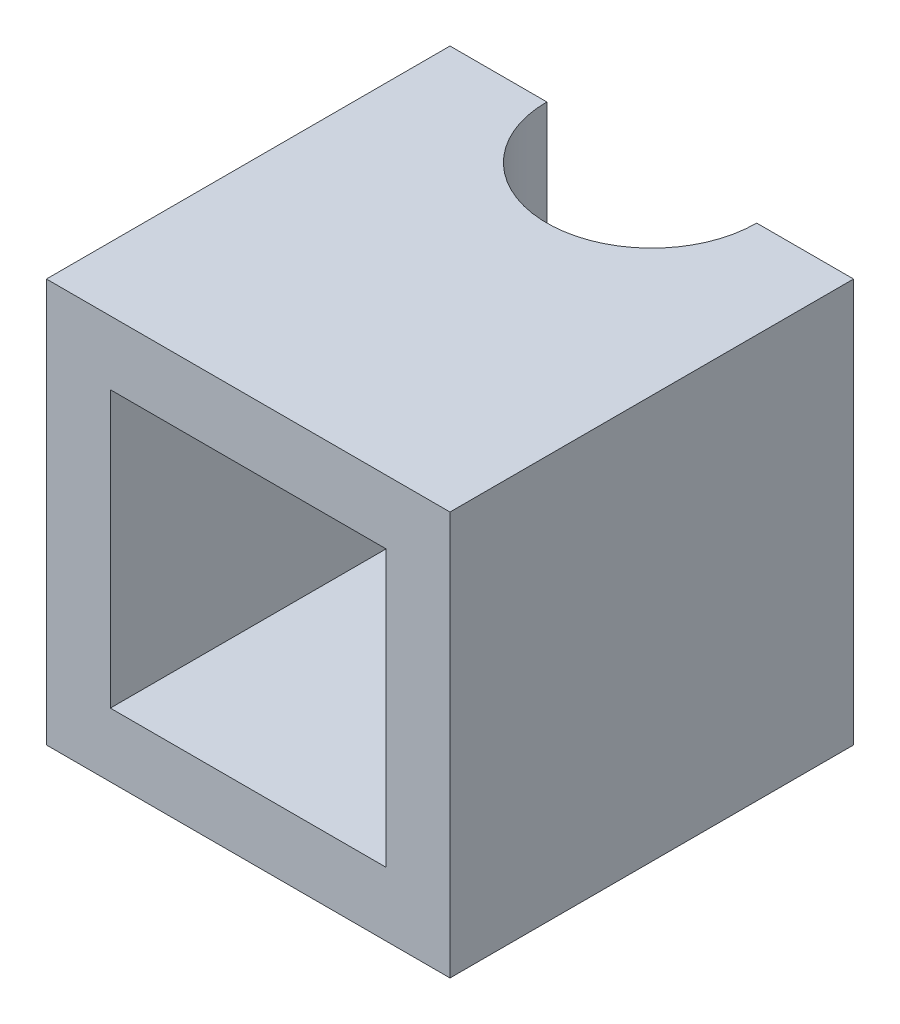
SolidWorks part; units mm, degrees
material "ABS"
ref_plane "Front Plane" through (0, 0, 0) normal (0, 0, 1) x (1, 0, 0)
ref_plane "Top Plane" through (0, 0, 0) normal (0, 1, 0) x (1, 0, 0)
ref_plane "Right Plane" through (0, 0, 0) normal (1, 0, 0) x (0, 0, -1)
sketch "Sketch1" plane through (0, 0, 0) normal (0, 0, 1) x (1, 0, 0)
  line L1 (-15, -15) -> (15, -15)
  line L2 (-15, -15) -> (-15, 15)
  line L3 (-15, 15) -> (15, 15)
  line L4 (15, -15) -> (15, 15)
  line L5 (-15, -15) -> (15, 15) construction
  line L6 (-15, 15) -> (15, -15) construction
  line L7 (-10.25, -10.25) -> (10.25, -10.25)
  line L8 (-10.25, -10.25) -> (-10.25, 10.25)
  line L9 (-10.25, 10.25) -> (10.25, 10.25)
  line L10 (10.25, -10.25) -> (10.25, 10.25)
  line L11 (-10.25, -10.25) -> (10.25, 10.25) construction
  line L12 (-10.25, 10.25) -> (10.25, -10.25) construction
  point P0 (0, 0)
  point P6 (0, 0)
  dimension "D1" = 30
  dimension "D2" = 20.5
  dimension "D3" = 20.5
extrude "Boss-Extrude1" add sketch "Sketch1" along normal blind 20
sketch "Sketch2" plane through (0, 0, 0) normal (0, 0, -1) x (-1, 0, 0)
  line L1 (-15, -15) -> (15, -15)
  line L2 (-15, -15) -> (-15, 15)
  line L3 (-15, 15) -> (15, 15)
  line L4 (15, -15) -> (15, 15)
  line L5 (-15, -15) -> (15, 15) construction
  line L6 (-15, 15) -> (15, -15) construction
  point P0 (0, 0)
extrude "Boss-Extrude3" add sketch "Sketch2" along normal blind 10
sketch "Sketch4" plane through (0, 0, -10) normal (0, 0, -1) x (-1, 0, 0)
  line L0 (0, 0) -> (0, 15)
  line L1 (15, 15) -> (-15, 15) construction
  line L2 (0, 15) -> (7.8, 15)
  line L3 (7.8, 15) -> (7.8, 8.75)
  line L10 (7.8, 7.65) -> (7.8, 8.75)
  line L19 (0, 0) -> (7.8, 0)
  line L20 (10.8, 9.95) -> (12.3, 9.95)
  line L21 (10.8, 9.95) -> (10.8, 6.45)
  line L22 (10.8, 6.45) -> (12.3, 6.45)
  line L23 (12.3, 9.95) -> (12.3, 6.45)
  line L24 (7.8, 0) -> (7.8, 7.65)
  dimension "D1" = 7.8
  dimension "D2" = 6.25
  dimension "D5" = 3
  dimension "D7" = 3.5
  dimension "D10" = 1.5
revolve "Cut-Revolve1" cut sketch "Sketch4" angle 180 about L0
sketch "Sketch5" plane through (0, 0, 0) normal (0, 0, 1) x (1, 0, 0)
  line L1 (-7.1617, 6.45) -> (7.1617, 6.45)
  line L2 (-7.1617, 6.45) -> (-7.1617, 9.95)
  line L3 (-7.1617, 9.95) -> (7.1617, 9.95)
  line L4 (7.1617, 6.45) -> (7.1617, 9.95)
extrude "Cut-Extrude2" cut sketch "Sketch5" against normal blind 1.5 contours L2 L1 L4 L3
mirror "Mirror1" about plane through (0, 0, -10) normal (0, -1, 0) of "Cut-Extrude2", "Cut-Revolve1"
sketch "Sketch6" plane through (0, 0, 0) normal (0, 0, 1) x (1, 0, 0)
  line L1 (10.25, -10.25) -> (-10.25, -10.25)
  line L2 (10.25, -10.25) -> (10.25, 10.25)
  line L3 (10.25, 10.25) -> (-10.25, 10.25)
  line L4 (-10.25, -10.25) -> (-10.25, 10.25)
extrude "Cut-Extrude3" cut sketch "Sketch6" against normal blind 2
